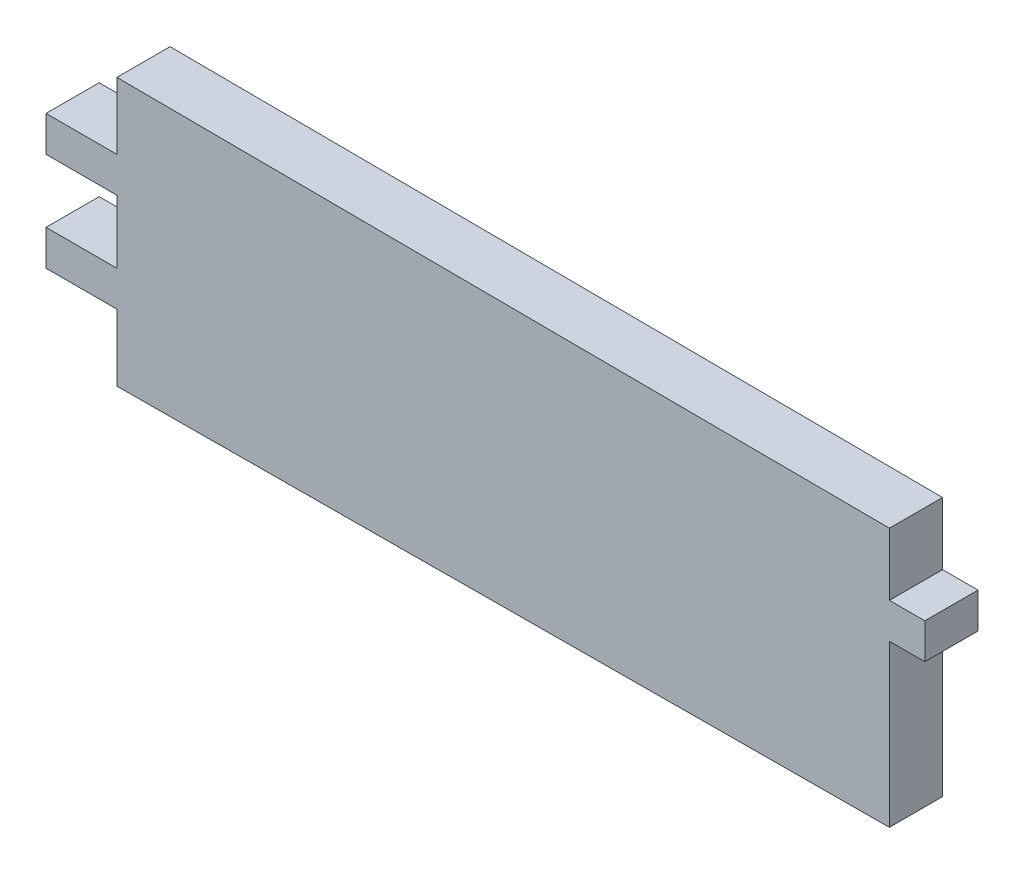
SolidWorks part; units mm, degrees
material "Balsa"
ref_plane "Front Plane" through (0, 0, 0) normal (0, 0, 1) x (1, 0, 0)
ref_plane "Top Plane" through (0, 0, 0) normal (0, 1, 0) x (1, 0, 0)
ref_plane "Right Plane" through (0, 0, 0) normal (1, 0, 0) x (0, 0, -1)
sketch "Sketch1" plane through (0, 0, 0) normal (0, 0, 1) x (1, 0, 0)
  line L0 (-75.8404, 8.2798) -> (-69.4904, 8.2798)
  line L1 (-69.4904, 8.2798) -> (-69.4904, 14.2526)
  line L2 (-75.8404, 8.2798) -> (-75.8404, 5.1048)
  line L3 (-75.8404, 5.1048) -> (-69.4904, 5.1048)
  line L4 (-69.4904, 5.1048) -> (-69.4904, -0.5594)
  line L5 (-69.4904, -0.5594) -> (-75.8404, -0.5594)
  line L6 (-75.8404, -0.5594) -> (-75.8404, -3.7344)
  line L7 (-75.8404, -3.7344) -> (-69.4904, -3.7344)
  line L8 (-69.4904, -3.7344) -> (-69.4904, -9.7072)
  line L9 (-0.2754, 8.2798) -> (2.8996, 8.2798)
  line L10 (2.8996, 8.2798) -> (2.8996, 5.1048)
  line L11 (2.8996, 5.1048) -> (-0.2754, 5.1048)
  line L12 (-0.2754, 5.1048) -> (-0.2754, -9.3334)
  line L13 (-0.2754, 8.2798) -> (-0.2754, 13.8789)
  line L14 (-69.4904, -9.7072) -> (-0.2754, -9.3334)
  line L15 (-69.4904, 14.2526) -> (-0.2754, 13.8789)
extrude "Boss-Extrude1" add sketch "Sketch1" along normal up to surface (4.7625 mm away)
